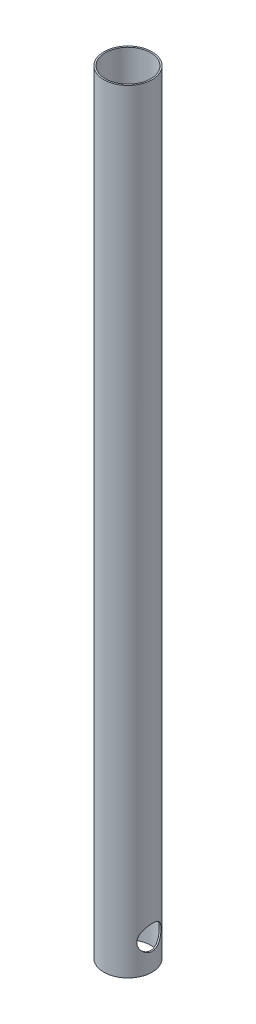
SolidWorks part; units mm, degrees
material "6061-T6 (SS)"
ref_plane "Front Plane" through (0, 0, 0) normal (0, 0, 1) x (1, 0, 0)
ref_plane "Top Plane" through (0, 0, 0) normal (0, 1, 0) x (1, 0, 0)
ref_plane "Right Plane" through (0, 0, 0) normal (1, 0, 0) x (0, 0, -1)
sketch "Sketch1" plane through (0, 0, 0) normal (0, 1, 0) x (1, 0, 0)
  circle A0 centre (0, 0) radius 25.4
  dimension "D1" = 50.8
extrude "Boss-Extrude1" add sketch "Sketch1" along normal mid plane 812.8
shell "Shell1" thickness 1.5875
ref_plane "Plane1" through (25.4, 0, 0) normal (1, 0, 0) x (0, 0, -1)
sketch "Sketch2" plane through (25.4, 0, 0) normal (1, 0, 0) x (0, 0, -1)
  line L0 (-25.4, -406.4) -> (25.4, -406.4) construction
  circle A0 centre (0, -374.65) radius 12.7
  point P4 (0, 0)
  dimension "D1" = 25.4
  dimension "D2" = 31.75
extrude "Cut-Extrude1" cut sketch "Sketch2" against normal through all
